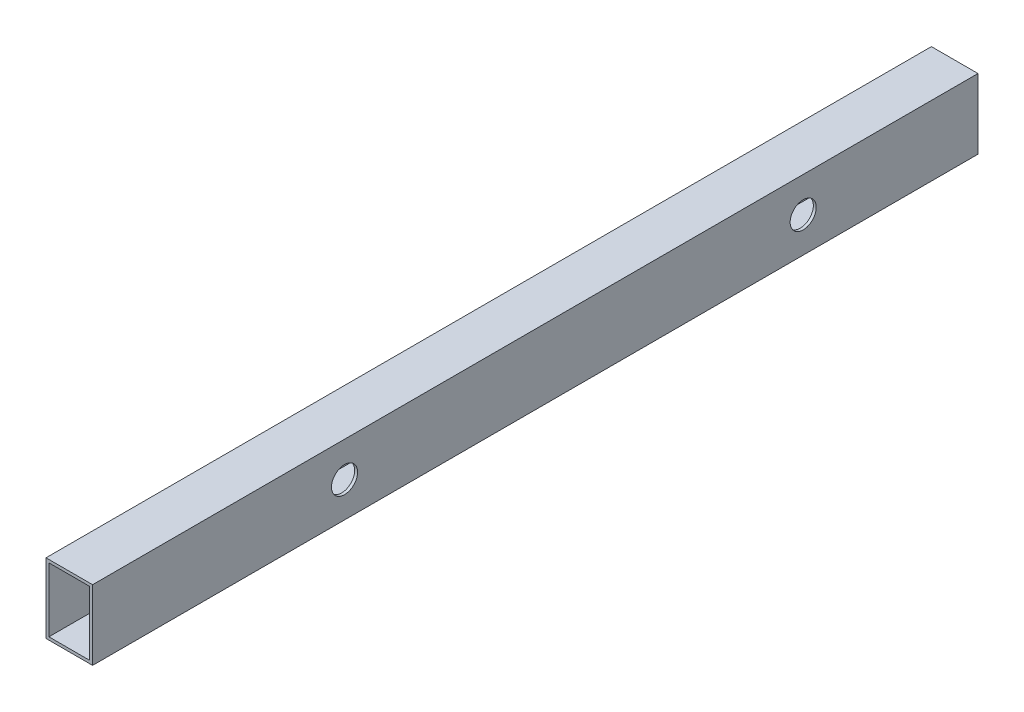
SolidWorks part; units mm, degrees
ref_plane "Front Plane" through (0, 0, 0) normal (0, 0, 1) x (1, 0, 0)
ref_plane "Top Plane" through (0, 0, 0) normal (0, 1, 0) x (1, 0, 0)
ref_plane "Right Plane" through (0, 0, 0) normal (1, 0, 0) x (0, 0, -1)
sketch "Sketch1" plane through (0, 0, 0) normal (0, 0, 1) x (1, 0, 0)
  line L0 (0, 38.1) -> (0, 34.925) construction
  line L1 (-25.4, 38.1) -> (25.4, 38.1)
  line L2 (-25.4, 38.1) -> (-25.4, -38.1)
  line L3 (-25.4, -38.1) -> (25.4, -38.1)
  line L4 (25.4, 38.1) -> (25.4, -38.1)
  line L5 (-25.4, 38.1) -> (25.4, -38.1) construction
  line L6 (-25.4, -38.1) -> (25.4, 38.1) construction
  line L7 (-22.225, 34.925) -> (22.225, 34.925)
  line L8 (-22.225, 34.925) -> (-22.225, -34.925)
  line L9 (-22.225, -34.925) -> (22.225, -34.925)
  line L10 (22.225, 34.925) -> (22.225, -34.925)
  line L11 (22.225, 0) -> (25.4, 0) construction
  line L12 (-22.225, 0) -> (-25.4, 0) construction
  line L13 (0, -34.925) -> (0, -38.1) construction
  point P0 (0, 0)
  dimension "D1" = 76.2
  dimension "D2" = 50.8
  dimension "D3" = 3.175
extrude "Boss-Extrude1" add sketch "Sketch1" along normal blind 965.2
sketch "Sketch2" plane through (0, 38.1, 0) normal (0, 1, 0) x (1, 0, 0)
  line L0 (-26.9875, -190.549) -> (26.9875, -190.549) construction
  line L1 (-25.4, 0) -> (25.4, 0)
  line L2 (-25.4, 0) -> (-25.4, -965.2)
  line L3 (-25.4, -965.2) -> (25.4, -965.2)
  line L4 (25.4, 0) -> (25.4, -965.2)
  line L5 (-26.4963, -703.2466) -> (26.4963, -703.2466) construction
  line L6 (0, -703.2466) -> (0, -190.549) construction
  line L7 (0, 0) -> (0, -190.549) construction
  line L8 (-74.6125, -402.6047) -> (-73.6301, -528.6965) construction
  line L9 (-74.1213, -465.6506) -> (-23.8125, -465.6506) construction
  line L10 (-23.8125, -465.6506) -> (26.9875, -465.6506) construction
  dimension "D1" = 190.549
  dimension "D2" = 512.6976
  dimension "D3" = 126.0917
  dimension "D4" = 50.3088
  dimension "D5" = 50.8
  dimension "D6" = 53.975
  dimension "D7" = 52.9926
  dimension "D8" = 275.1016
ref_plane "Plane1" through (25.4, 0, 0) normal (1, 0, 0) x (0, 0, -1)
sketch "Sketch4" plane through (25.4, 0, 0) normal (1, 0, 0) x (0, 0, -1)
  line L0 (-690.548, 38.1) -> (-690.548, 0) construction
  line L1 (-703.2466, 38.1) -> (-190.549, 38.1) construction
  line L2 (-190.549, 38.1) -> (-190.549, 0) construction
  line L3 (0, 38.1) -> (-190.549, 38.1) construction
  line L4 (-190.549, 0) -> (0, 0) construction
  line L5 (0, -38.1) -> (0, 38.1) construction
  line L6 (-190.549, 0) -> (-690.548, 0) construction
  circle A0 centre (-690.548, 0) radius 14.224
  circle A1 centre (-190.549, 0) radius 14.224
  dimension "D1" = 28.448
  dimension "D2" = 499.999
  dimension "D3" = 190.549
extrude "Cut-Extrude1" cut sketch "Sketch4" against normal up to surface (50.8 mm away) contours A1 | A0 up to face at (-25.4, 0, 482.6)
